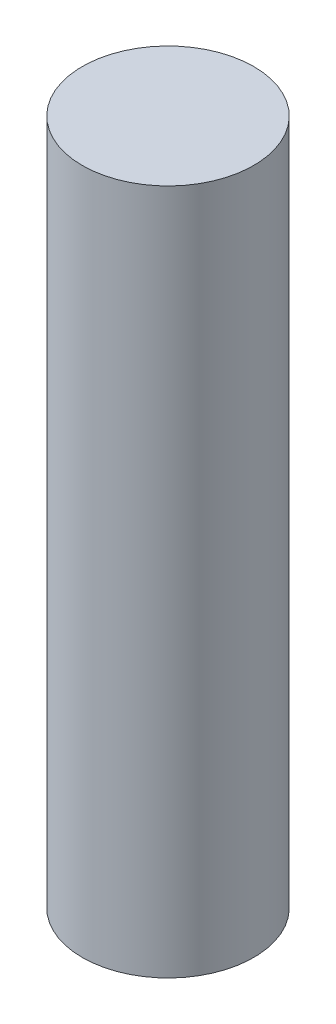
SolidWorks part; units mm, degrees
ref_plane "Front Plane" through (0, 0, 0) normal (0, 0, 1) x (1, 0, 0)
ref_plane "Top Plane" through (0, 0, 0) normal (0, 1, 0) x (1, 0, 0)
ref_plane "Right Plane" through (0, 0, 0) normal (1, 0, 0) x (0, 0, -1)
sketch "Sketch1" plane through (0, 0, 0) normal (0, 1, 0) x (1, 0, 0)
  circle A0 centre (0, 0) radius 9.525
  dimension "D1" = 19.05
extrude "Boss-Extrude1" add sketch "Sketch1" along normal blind 76.2
